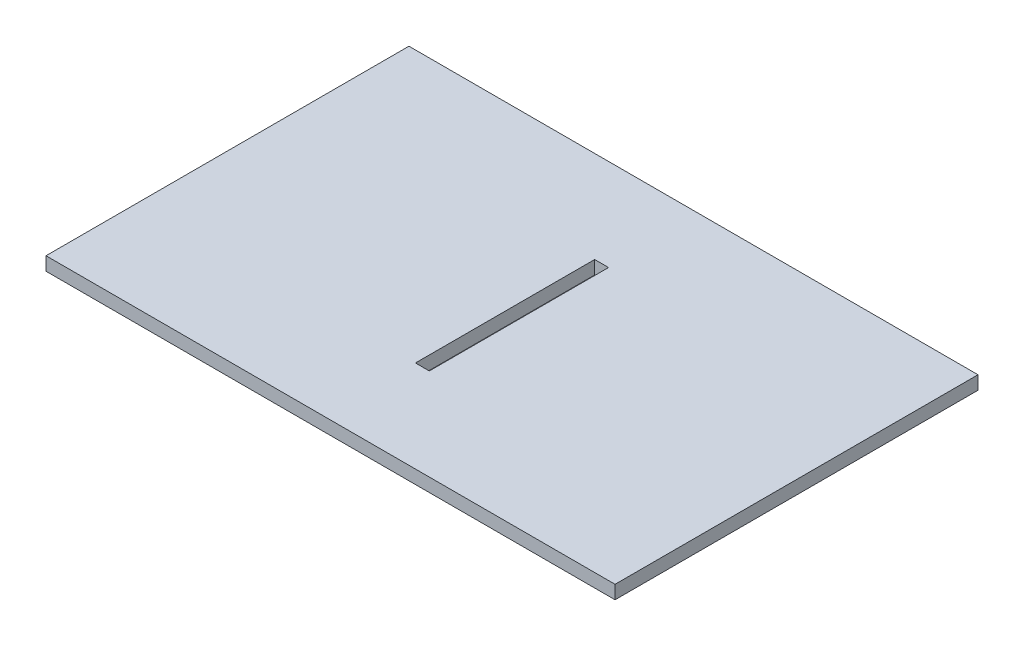
SolidWorks part; units mm, degrees
material "PPS"
ref_plane "Front Plane" through (0, 0, 0) normal (0, 0, 1) x (1, 0, 0)
ref_plane "Top Plane" through (0, 0, 0) normal (0, 1, 0) x (1, 0, 0)
ref_plane "Right Plane" through (0, 0, 0) normal (1, 0, 0) x (0, 0, -1)
sketch "Sketch1" plane through (0, 0, 0) normal (0, 1, 0) x (1, 0, 0)
  line L1 (-31.75, -20.25) -> (31.75, -20.25)
  line L2 (-31.75, -20.25) -> (-31.75, 20.25)
  line L3 (-31.75, 20.25) -> (31.75, 20.25)
  line L4 (31.75, -20.25) -> (31.75, 20.25)
  line L5 (0, 20.25) -> (0, -20.25) construction
  line L6 (-31.75, 0) -> (31.75, 0) construction
  line L7 (-0.775, -10) -> (0.775, -10)
  line L8 (-0.775, -10) -> (-0.775, 10)
  line L9 (-0.775, 10) -> (0.775, 10)
  line L10 (0.775, -10) -> (0.775, 10)
  line L11 (0, 10) -> (0, -10) construction
  line L12 (-0.775, 0) -> (0.775, 0) construction
  point P0 (0, 0)
  point P4 (0, 0)
  dimension "D1" = 1.55
  dimension "D2" = 20
  dimension "D3" = 40.5
  dimension "D4" = 63.5
extrude "Boss-Extrude1" add sketch "Sketch1" along normal blind 1.5
